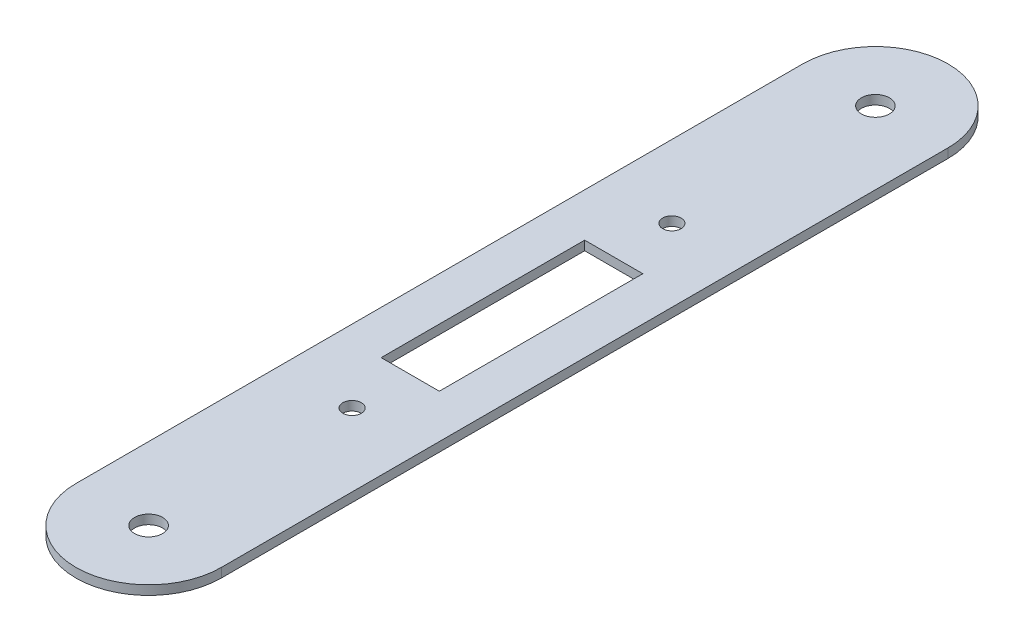
SolidWorks part; units mm, degrees
ref_plane "Front" through (0, 0, 0) normal (0, 0, 1) x (1, 0, 0)
ref_plane "Top" through (0, 0, 0) normal (0, 1, 0) x (1, 0, 0)
ref_plane "Right" through (0, 0, 0) normal (1, 0, 0) x (0, 0, -1)
sketch "Sketch1" plane through (0, 0, 0) normal (0, 1, 0) x (1, 0, 0)
  line L0 (25, 0) -> (25, -300) construction
  line L1 (0, 0) -> (50, 0)
  line L2 (0, 0) -> (0, -300)
  line L3 (0, -300) -> (50, -300)
  line L4 (50, 0) -> (50, -300)
  line L5 (0, -150) -> (50, -150) construction
  line L7 (15, -115) -> (35, -115)
  line L8 (15, -115) -> (15, -185)
  line L9 (15, -185) -> (35, -185)
  line L10 (35, -115) -> (35, -185)
  circle A0 centre (25, -25) radius 4.82
  circle A1 centre (25, -275) radius 4.82
  circle A2 centre (25, -25) radius 25
  circle A3 centre (25, -275) radius 25
  circle A4 centre (25, -95) radius 3.175
  circle A5 centre (25, -205) radius 3.175
  dimension "D3" = 9.64
  dimension "D4" = 25
  dimension "D7" = 6.35
  dimension "D1" = 50
  dimension "D2" = 300
  dimension "D5" = 70
  dimension "D6" = 20
  dimension "D8" = 55
extrude "Boss-Extrude1" add sketch "Sketch1" along normal blind 3.175 contours A3 L4 A2 L2 | A3 A1 | A2 A0
